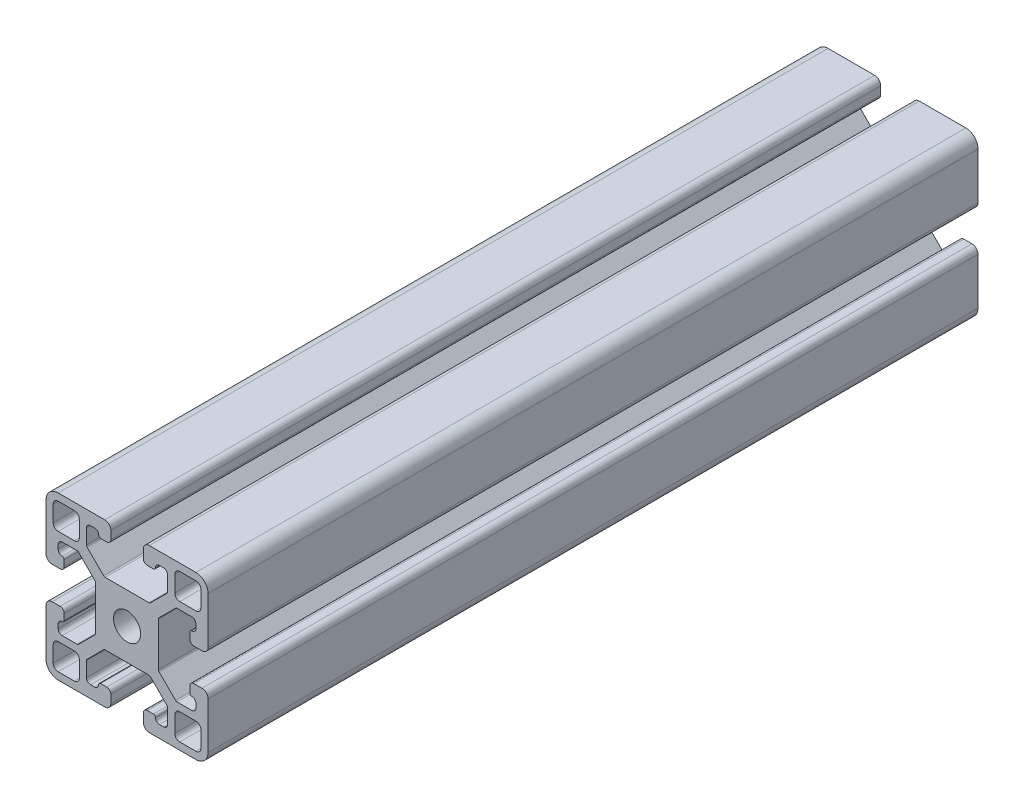
SolidWorks part; units mm, degrees
ref_plane "Front Plane" through (0, 0, 0) normal (0, 0, 1) x (1, 0, 0)
ref_plane "Top Plane" through (0, 0, 0) normal (0, 1, 0) x (1, 0, 0)
ref_plane "Right Plane" through (0, 0, 0) normal (1, 0, 0) x (0, 0, -1)
sketch "Sketch1" plane through (0, 0, 0) normal (0, 0, 1) x (1, 0, 0)
  line B0 (-17, 11.78) -> (-13, 11.78)
  arc B1 (-13, 11.78) -> (-11.78, 13) centre (-13, 13) ccw
  line B2 (-11.78, 13) -> (-11.78, 17)
  arc B3 (-11.78, 17) -> (-13, 18.22) centre (-13, 17) ccw
  line B4 (-13, 18.22) -> (-17, 18.22)
  arc B5 (-17, 18.22) -> (-18.22, 17) centre (-17, 17) ccw
  line B6 (-18.22, 17) -> (-18.22, 13)
  arc B7 (-18.22, 13) -> (-17, 11.78) centre (-17, 13) ccw
  line B8 (-18.22, -13) -> (-18.22, -17)
  arc B9 (-18.22, -17) -> (-17, -18.22) centre (-17, -17) ccw
  line B10 (-17, -18.22) -> (-13, -18.22)
  arc B11 (-13, -18.22) -> (-11.78, -17) centre (-13, -17) ccw
  line B12 (-11.78, -17) -> (-11.78, -13)
  arc B13 (-11.78, -13) -> (-13, -11.78) centre (-13, -13) ccw
  line B14 (-13, -11.78) -> (-17, -11.78)
  arc B15 (-17, -11.78) -> (-18.22, -13) centre (-17, -13) ccw
  line B16 (13, -18.22) -> (17, -18.22)
  arc B17 (17, -18.22) -> (18.22, -17) centre (17, -17) ccw
  line B18 (18.22, -17) -> (18.22, -13)
  arc B19 (18.22, -13) -> (17, -11.78) centre (17, -13) ccw
  line B20 (17, -11.78) -> (13, -11.78)
  arc B21 (13, -11.78) -> (11.78, -13) centre (13, -13) ccw
  line B22 (11.78, -13) -> (11.78, -17)
  arc B23 (11.78, -17) -> (13, -18.22) centre (13, -17) ccw
  line B24 (18.22, 13) -> (18.22, 17)
  arc B25 (18.22, 17) -> (17, 18.22) centre (17, 17) ccw
  line B26 (17, 18.22) -> (13, 18.22)
  arc B27 (13, 18.22) -> (11.78, 17) centre (13, 17) ccw
  line B28 (11.78, 17) -> (11.78, 13)
  arc B29 (11.78, 13) -> (13, 11.78) centre (13, 13) ccw
  line B30 (13, 11.78) -> (17, 11.78)
  arc B31 (17, 11.78) -> (18.22, 13) centre (17, 13) ccw
  line B32 (-9.8536, -11.9786) -> (-5.7714, -7.8964)
  arc B33 (-5.4179, -7.75) -> (-5.7714, -7.8964) centre (-5.4179, -8.25) ccw
  line B34 (-5.4179, -7.75) -> (5.4179, -7.75)
  arc B35 (5.7714, -7.8964) -> (5.4179, -7.75) centre (5.4179, -8.25) ccw
  line B36 (5.7714, -7.8964) -> (9.8536, -11.9786)
  arc B37 (10, -12.3321) -> (9.8536, -11.9786) centre (9.5, -12.3321) ccw
  line B38 (10, -12.3321) -> (10, -16)
  arc B39 (9, -17) -> (10, -16) centre (9, -16) ccw
  line B40 (9, -17) -> (8, -17)
  arc B41 (7, -16) -> (8, -17) centre (8, -16) ccw
  arc B42 (7, -16) -> (6.5, -15.5) centre (6.5, -16) ccw
  line B43 (6.5, -15.5) -> (5, -15.5)
  arc B44 (5, -15.5) -> (4, -16.5) centre (5, -16.5) ccw
  line B45 (4, -16.5) -> (4, -18.5)
  arc B46 (4, -18.5) -> (5.5, -20) centre (5.5, -18.5) ccw
  line B47 (5.5, -20) -> (17, -20)
  arc B48 (17, -20) -> (20, -17) centre (17, -17) ccw
  line B49 (20, -17) -> (20, -5.5)
  arc B50 (20, -5.5) -> (18.5, -4) centre (18.5, -5.5) ccw
  line B51 (18.5, -4) -> (16.5, -4)
  arc B52 (16.5, -4) -> (15.5, -5) centre (16.5, -5) ccw
  line B53 (15.5, -5) -> (15.5, -6.5)
  arc B54 (15.5, -6.5) -> (16, -7) centre (16, -6.5) ccw
  arc B55 (17, -8) -> (16, -7) centre (16, -8) ccw
  line B56 (17, -8) -> (17, -9)
  arc B57 (16, -10) -> (17, -9) centre (16, -9) ccw
  line B58 (16, -10) -> (12.3321, -10)
  arc B59 (11.9786, -9.8536) -> (12.3321, -10) centre (12.3321, -9.5) ccw
  line B60 (11.9786, -9.8536) -> (7.8964, -5.7714)
  arc B61 (7.75, -5.4179) -> (7.8964, -5.7714) centre (8.25, -5.4179) ccw
  line B62 (7.75, -5.4179) -> (7.75, 5.4179)
  arc B63 (7.8964, 5.7714) -> (7.75, 5.4179) centre (8.25, 5.4179) ccw
  line B64 (7.8964, 5.7714) -> (11.9786, 9.8536)
  arc B65 (12.3321, 10) -> (11.9786, 9.8536) centre (12.3321, 9.5) ccw
  line B66 (12.3321, 10) -> (16, 10)
  arc B67 (17, 9) -> (16, 10) centre (16, 9) ccw
  line B68 (17, 9) -> (17, 8)
  arc B69 (16, 7) -> (17, 8) centre (16, 8) ccw
  arc B70 (16, 7) -> (15.5, 6.5) centre (16, 6.5) ccw
  line B71 (15.5, 6.5) -> (15.5, 5)
  arc B72 (15.5, 5) -> (16.5, 4) centre (16.5, 5) ccw
  line B73 (16.5, 4) -> (18.5, 4)
  arc B74 (18.5, 4) -> (20, 5.5) centre (18.5, 5.5) ccw
  line B75 (20, 5.5) -> (20, 17)
  arc B76 (20, 17) -> (17, 20) centre (17, 17) ccw
  line B77 (17, 20) -> (5.5, 20)
  arc B78 (5.5, 20) -> (4, 18.5) centre (5.5, 18.5) ccw
  line B79 (4, 18.5) -> (4, 16.5)
  arc B80 (4, 16.5) -> (5, 15.5) centre (5, 16.5) ccw
  line B81 (5, 15.5) -> (6.5, 15.5)
  arc B82 (6.5, 15.5) -> (7, 16) centre (6.5, 16) ccw
  arc B83 (8, 17) -> (7, 16) centre (8, 16) ccw
  line B84 (8, 17) -> (9, 17)
  arc B85 (10, 16) -> (9, 17) centre (9, 16) ccw
  line B86 (10, 16) -> (10, 12.3321)
  arc B87 (9.8536, 11.9786) -> (10, 12.3321) centre (9.5, 12.3321) ccw
  line B88 (9.8536, 11.9786) -> (5.7714, 7.8964)
  arc B89 (5.4179, 7.75) -> (5.7714, 7.8964) centre (5.4179, 8.25) ccw
  line B90 (5.4179, 7.75) -> (-5.4179, 7.75)
  arc B91 (-5.7714, 7.8964) -> (-5.4179, 7.75) centre (-5.4179, 8.25) ccw
  line B92 (-5.7714, 7.8964) -> (-9.8536, 11.9786)
  arc B93 (-10, 12.3321) -> (-9.8536, 11.9786) centre (-9.5, 12.3321) ccw
  line B94 (-10, 12.3321) -> (-10, 16)
  arc B95 (-9, 17) -> (-10, 16) centre (-9, 16) ccw
  line B96 (-9, 17) -> (-8, 17)
  arc B97 (-7, 16) -> (-8, 17) centre (-8, 16) ccw
  arc B98 (-7, 16) -> (-6.5, 15.5) centre (-6.5, 16) ccw
  line B99 (-6.5, 15.5) -> (-5, 15.5)
  arc B100 (-5, 15.5) -> (-4, 16.5) centre (-5, 16.5) ccw
  line B101 (-4, 16.5) -> (-4, 18.5)
  arc B102 (-4, 18.5) -> (-5.5, 20) centre (-5.5, 18.5) ccw
  line B103 (-5.5, 20) -> (-17, 20)
  arc B104 (-17, 20) -> (-20, 17) centre (-17, 17) ccw
  line B105 (-20, 17) -> (-20, 5.5)
  arc B106 (-20, 5.5) -> (-18.5, 4) centre (-18.5, 5.5) ccw
  line B107 (-18.5, 4) -> (-16.5, 4)
  arc B108 (-16.5, 4) -> (-15.5, 5) centre (-16.5, 5) ccw
  line B109 (-15.5, 5) -> (-15.5, 6.5)
  arc B110 (-15.5, 6.5) -> (-16, 7) centre (-16, 6.5) ccw
  arc B111 (-17, 8) -> (-16, 7) centre (-16, 8) ccw
  line B112 (-17, 8) -> (-17, 9)
  arc B113 (-16, 10) -> (-17, 9) centre (-16, 9) ccw
  line B114 (-16, 10) -> (-12.3321, 10)
  arc B115 (-11.9786, 9.8536) -> (-12.3321, 10) centre (-12.3321, 9.5) ccw
  line B116 (-11.9786, 9.8536) -> (-7.8964, 5.7714)
  arc B117 (-7.75, 5.4179) -> (-7.8964, 5.7714) centre (-8.25, 5.4179) ccw
  line B118 (-7.75, 5.4179) -> (-7.75, -5.4179)
  arc B119 (-7.8964, -5.7714) -> (-7.75, -5.4179) centre (-8.25, -5.4179) ccw
  line B120 (-7.8964, -5.7714) -> (-11.9786, -9.8536)
  arc B121 (-12.3321, -10) -> (-11.9786, -9.8536) centre (-12.3321, -9.5) ccw
  line B122 (-12.3321, -10) -> (-16, -10)
  arc B123 (-17, -9) -> (-16, -10) centre (-16, -9) ccw
  line B124 (-17, -9) -> (-17, -8)
  arc B125 (-16, -7) -> (-17, -8) centre (-16, -8) ccw
  arc B126 (-16, -7) -> (-15.5, -6.5) centre (-16, -6.5) ccw
  line B127 (-15.5, -6.5) -> (-15.5, -5)
  arc B128 (-15.5, -5) -> (-16.5, -4) centre (-16.5, -5) ccw
  line B129 (-16.5, -4) -> (-18.5, -4)
  arc B130 (-18.5, -4) -> (-20, -5.5) centre (-18.5, -5.5) ccw
  line B131 (-20, -5.5) -> (-20, -17)
  arc B132 (-20, -17) -> (-17, -20) centre (-17, -17) ccw
  line B133 (-17, -20) -> (-5.5, -20)
  arc B134 (-5.5, -20) -> (-4, -18.5) centre (-5.5, -18.5) ccw
  line B135 (-4, -18.5) -> (-4, -16.5)
  arc B136 (-4, -16.5) -> (-5, -15.5) centre (-5, -16.5) ccw
  line B137 (-5, -15.5) -> (-6.5, -15.5)
  arc B138 (-6.5, -15.5) -> (-7, -16) centre (-6.5, -16) ccw
  arc B139 (-8, -17) -> (-7, -16) centre (-8, -16) ccw
  line B140 (-8, -17) -> (-9, -17)
  arc B141 (-10, -16) -> (-9, -17) centre (-9, -16) ccw
  line B142 (-10, -16) -> (-10, -12.3321)
  arc B143 (-9.8536, -11.9786) -> (-10, -12.3321) centre (-9.5, -12.3321) ccw
  circle B144 centre (0, 0) radius 3.35
sketch_block_instance "S8-4040 - S-1"
sketch_block "S8-4040 - S"
extrude "Boss-Extrude1" add sketch "Sketch1" along normal blind 190
